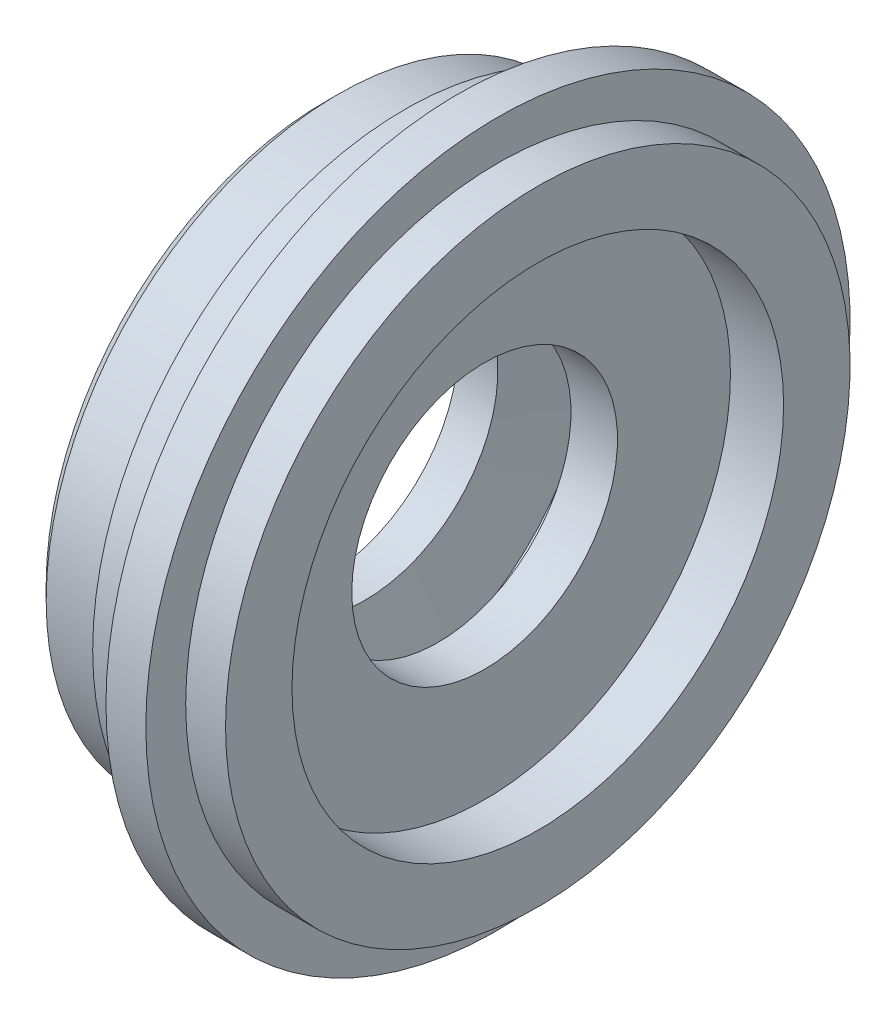
SolidWorks part; units mm, degrees
ref_plane "前视基准面" through (0, 0, 0) normal (0, 0, 1) x (1, 0, 0)
ref_plane "上视基准面" through (0, 0, 0) normal (0, 1, 0) x (1, 0, 0)
ref_plane "右视基准面" through (0, 0, 0) normal (1, 0, 0) x (0, 0, -1)
sketch "草图1" plane through (0, 0, 0) normal (0, 0, 1) x (1, 0, 0)
  line L0 (0, 0) -> (10.9922, 0) construction
  line L1 (0, 10) -> (0, 21)
  line L2 (1, 22) -> (6, 22)
  line L3 (6, 22) -> (6, 23.5)
  line L4 (6, 23.5) -> (10, 23.5)
  line L5 (10, 23.5) -> (10, 26.5)
  line L6 (10, 26.5) -> (13, 26.5)
  line L7 (13, 26.5) -> (13, 23.5)
  line L8 (13, 23.5) -> (16, 23.5)
  line L9 (16, 23.5) -> (16, 18.5)
  line L10 (16, 18.5) -> (12, 18.5)
  line L11 (12, 18.5) -> (12, 10)
  line L12 (12, 10) -> (8.5, 10)
  line L14 (7.75, 16.5) -> (3.75, 16.5)
  line L15 (3.75, 16.5) -> (3, 10)
  line L16 (3, 10) -> (0, 10)
  line L17 (5.75, 16.5) -> (5.75, 13.7887)
  line L18 (7.75, 16.5) -> (8.5, 10)
  line L19 (0, 21) -> (1, 22)
  point P4 (0, 22)
  point P5 (8, 23.5)
  dimension "D1" = 53
  dimension "D2" = 37
  dimension "D3" = 47
  dimension "D4" = 44
  dimension "D5" = 33
  dimension "D6" = 20
  dimension "D7" = 4
  dimension "D8" = 5.5
  dimension "D9" = 3
  dimension "D10" = 4
  dimension "D11" = 3
  dimension "D12" = 6
  dimension "D13" = 10
  dimension "D14" = 16
revolve "旋转1" add sketch "草图1" angle 360 about L0
